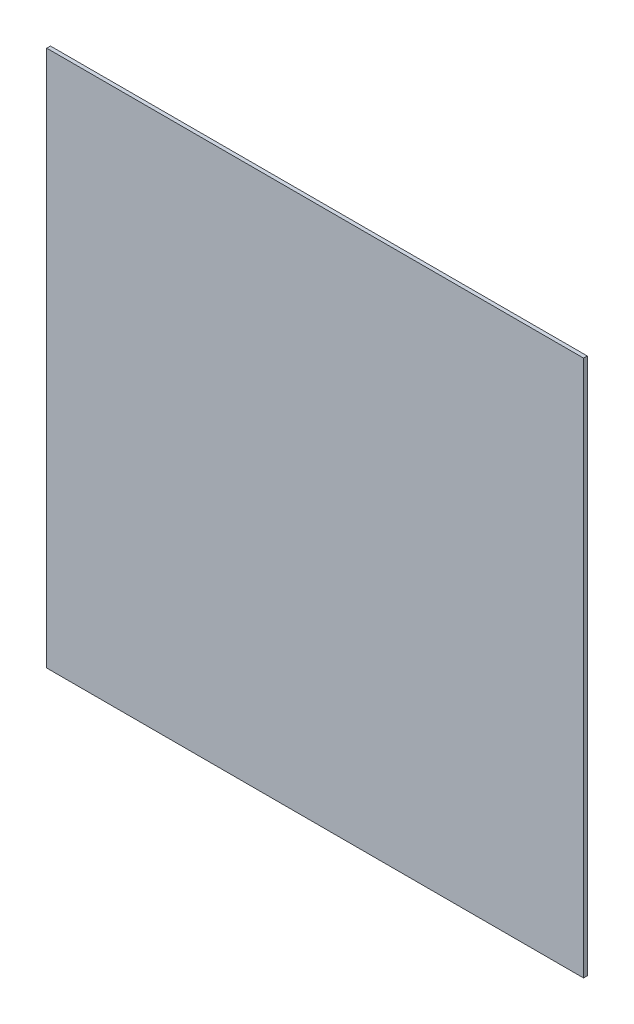
SolidWorks part; units mm, degrees
material "Custom Plastic"
ref_plane "X-Y Datum" through (0, 0, 0) normal (0, 0, 1) x (1, 0, 0)
ref_plane "X-Z Datum" through (0, 0, 0) normal (0, 1, 0) x (1, 0, 0)
ref_plane "Y-Z Datum" through (0, 0, 0) normal (1, 0, 0) x (0, 0, -1)
sketch "Sketch2" plane through (0, 0, 0) normal (0, 0, 1) x (1, 0, 0)
  line L1 (-457.2, 457.2) -> (457.2, 457.2)
  line L2 (-457.2, 457.2) -> (-457.2, -457.2)
  line L3 (-457.2, -457.2) -> (457.2, -457.2)
  line L4 (457.2, 457.2) -> (457.2, -457.2)
  line L5 (-457.2, 457.2) -> (457.2, -457.2) construction
  line L6 (-457.2, -457.2) -> (457.2, 457.2) construction
  point P0 (0, 0)
  dimension "D1" = 914.4
  dimension "D2" = 914.4
extrude "Boss-Extrude1" add sketch "Sketch2" along normal blind 6.35
